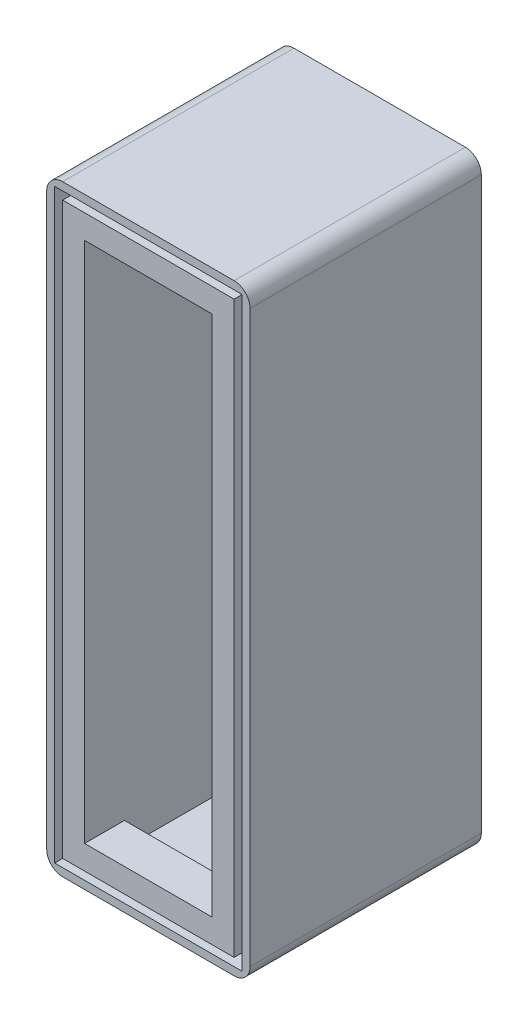
SolidWorks part; units mm, degrees
ref_plane "Front Plane" through (0, 0, 0) normal (0, 0, 1) x (1, 0, 0)
ref_plane "Top Plane" through (0, 0, 0) normal (0, 1, 0) x (1, 0, 0)
ref_plane "Right Plane" through (0, 0, 0) normal (1, 0, 0) x (0, 0, -1)
sketch "Sketch1" plane through (0, 0, 0) normal (0, 0, 1) x (1, 0, 0)
  line L1 (-5.9539, 27.3478) -> (19.5461, 27.3478)
  line L2 (-5.9539, 27.3478) -> (-5.9539, -48.1522)
  line L3 (-5.9539, -48.1522) -> (19.5461, -48.1522)
  line L4 (19.5461, 27.3478) -> (19.5461, -48.1522)
  dimension "D1" = 75.5
  dimension "D2" = 25.5
extrude "main body" add sketch "Sketch1" along normal blind 29
sketch "Sketch2" plane through (0, 0, 29) normal (0, 0, 1) x (1, 0, 0)
  line L0 (19.5461, -48.1522) -> (19.5461, 27.3478) construction
  line L1 (-1.2039, 25.3478) -> (14.7961, 25.3478)
  line L2 (-1.2039, 25.3478) -> (-1.2039, -46.1522)
  line L3 (-1.2039, -46.1522) -> (14.7961, -46.1522)
  line L4 (14.7961, 25.3478) -> (14.7961, -46.1522)
  line L5 (19.5461, 27.3478) -> (-5.9539, 27.3478) construction
  line L6 (-5.9539, -48.1522) -> (19.5461, -48.1522) construction
  dimension "D1" = 16
  dimension "D2" = 4.75
  dimension "D3" = 2
  dimension "D4" = 2
extrude "battery cut" cut sketch "Sketch2" against normal blind 17
sketch "Sketch3" plane through (0, 0, 0) normal (0, 0, -1) x (-1, 0, 0)
  line L0 (-19.5461, -48.1522) -> (-19.5461, 27.3478) construction
  line L1 (-17.7961, 25.3478) -> (4.2039, 25.3478)
  line L2 (-17.7961, 25.3478) -> (-17.7961, -46.1522)
  line L3 (-17.7961, -46.1522) -> (4.2039, -46.1522)
  line L4 (4.2039, 25.3478) -> (4.2039, -46.1522)
  line L5 (-19.5461, 27.3478) -> (5.9539, 27.3478) construction
  dimension "D1" = 22
  dimension "D2" = 71.5
  dimension "D3" = 1.75
  dimension "D4" = 2
extrude "pcb cut" cut sketch "Sketch3" against normal blind 12
sketch "Sketch4" plane through (0, 0, 0) normal (0, 0, -1) x (-1, 0, 0)
  line L0 (5.9539, 27.3478) -> (5.9539, -48.1522) construction
  line L1 (-18.4211, 16.4728) -> (4.8289, 16.4728)
  line L2 (-18.4211, 16.4728) -> (-18.4211, -47.0272)
  line L3 (-18.4211, -47.0272) -> (4.8289, -47.0272)
  line L4 (4.8289, 16.4728) -> (4.8289, -47.0272)
  line L5 (5.9539, -48.1522) -> (-19.5461, -48.1522) construction
  dimension "D1" = 23.25
  dimension "D2" = 1.125
  dimension "D3" = 1.125
  dimension "D4" = 63.5
extrude "solar cut" cut sketch "Sketch4" against normal blind 2
sketch "Sketch5" plane through (0, 0, 0) normal (0, 0, -1) x (-1, 0, 0)
  line L1 (-17.7961, 25.3478) -> (4.2039, 25.3478)
  line L2 (-17.7961, 25.3478) -> (-17.7961, 16.4728)
  line L3 (-17.7961, 16.4728) -> (4.2039, 16.4728)
  line L4 (4.2039, 25.3478) -> (4.2039, 16.4728)
extrude "solar gap fill" add sketch "Sketch5" against normal blind 2 separate body
sketch "Sketch6" plane through (0, -48.1522, 0) normal (0, -1, 0) x (1, 0, 0)
  line L0 (9.7961, 7.25) -> (3.7961, 7.25) construction
  line L1 (9.7961, 5.5) -> (3.7961, 5.5)
  line L2 (9.7961, 9) -> (3.7961, 9)
  line L3 (17.7961, 12) -> (14.7961, 12) construction
  line L4 (-5.9539, 29) -> (-5.9539, 0) construction
  line L5 (19.5461, 29) -> (19.5461, 0) construction
  arc A0 (9.7961, 5.5) -> (9.7961, 9) centre (9.7961, 7.25) ccw
  arc A1 (3.7961, 9) -> (3.7961, 5.5) centre (3.7961, 7.25) ccw
  point P2 (6.7961, 7.25)
  dimension "D4" = 9.75
  dimension "D5" = 9.75
  dimension "D1" = 3.5
  dimension "D2" = 6
  dimension "D3" = 3
extrude "USB cut" cut sketch "Sketch6" against normal blind 2
sketch "Sketch7" plane through (0, -48.1522, 0) normal (0, -1, 0) x (1, 0, 0)
  line L0 (9.2961, 7.25) -> (4.2961, 7.25) construction
  line L1 (9.2961, 3.75) -> (4.2961, 3.75)
  line L2 (9.2961, 10.75) -> (4.2961, 10.75)
  line L4 (-5.9539, 29) -> (-5.9539, 0) construction
  line L5 (9.7961, 9) -> (3.7961, 9) construction
  line L6 (3.7961, 5.5) -> (9.7961, 5.5) construction
  arc A0 (9.2961, 3.75) -> (9.2961, 10.75) centre (9.2961, 7.25) ccw
  arc A1 (4.2961, 10.75) -> (4.2961, 3.75) centre (4.2961, 7.25) ccw
  point P2 (6.7961, 7.25)
  dimension "D4" = 10.25
  dimension "D1" = 7
  dimension "D2" = 5
  dimension "D3" = 1.75
  dimension "D5" = 1.75
extrude "USB clearance emboss" cut sketch "Sketch7" against normal blind 1
fillet "Fillet1" radius 2 4 edges at (19.5461, 27.3478, 14.5) (-5.9539, 27.3478, 14.5) (19.5461, -48.1522, 14.5) (-5.9539, -48.1522, 14.5)
sketch "Sketch9" plane through (0, 0, 29) normal (0, 0, 1) x (1, 0, 0)
  line L0 (-5.9539, 25.3478) -> (-5.9539, -46.1522) construction
  line L1 (-4.9539, 26.3478) -> (18.5461, 26.3478)
  line L2 (-4.9539, 26.3478) -> (-4.9539, -47.1522)
  line L3 (-4.9539, -47.1522) -> (18.5461, -47.1522)
  line L4 (18.5461, 26.3478) -> (18.5461, -47.1522)
  line L5 (19.5461, -46.1522) -> (19.5461, 25.3478) construction
  line L6 (-3.9539, -48.1522) -> (17.5461, -48.1522) construction
  line L7 (17.5461, 27.3478) -> (-3.9539, 27.3478) construction
  line L9 (-3.9539, 25.3478) -> (17.5461, 25.3478)
  line L10 (-3.9539, 25.3478) -> (-3.9539, -46.1522)
  line L11 (-3.9539, -46.1522) -> (17.5461, -46.1522)
  line L12 (17.5461, 25.3478) -> (17.5461, -46.1522)
  dimension "D1" = 1
  dimension "D2" = 1
  dimension "D3" = 1
  dimension "D4" = 1
  dimension "D5" = 1
  dimension "D6" = 1
  dimension "D7" = 1
  dimension "D8" = 1
extrude "Cut-Extrude7" cut sketch "Sketch9" against normal blind 2
sketch "Sketch10" plane through (0, 0, 29) normal (0, 0, 1) x (1, 0, 0)
  line L0 (14.7961, -46.1522) -> (14.7961, 25.3478) construction
  line L1 (-1.2039, 25.3478) -> (14.7961, 25.3478)
  line L2 (-1.2039, 25.3478) -> (-1.2039, 22.3478)
  line L3 (-1.2039, 22.3478) -> (14.7961, 22.3478)
  line L4 (14.7961, 25.3478) -> (14.7961, 22.3478)
  line L6 (-1.2039, -46.1522) -> (14.7961, -46.1522)
  line L7 (-1.2039, -46.1522) -> (-1.2039, -43.1522)
  line L8 (-1.2039, -43.1522) -> (14.7961, -43.1522)
  line L9 (14.7961, -46.1522) -> (14.7961, -43.1522)
  dimension "D1" = 3
  dimension "D2" = 3
extrude "Boss-Extrude3" add sketch "Sketch10" against normal blind 5
sketch "Sketch11" plane through (0, 0, 2) normal (0, 0, 1) x (1, 0, 0)
  line L0 (-4.2039, 25.3478) -> (17.7961, 25.3478) construction
  line L1 (17.5914, 25.3478) -> (-4.2039, 25.3478)
  line L2 (17.5914, 25.3478) -> (17.5914, 15.9728)
  line L3 (17.5914, 15.9728) -> (-4.2039, 15.9728)
  line L4 (-4.2039, 25.3478) -> (-4.2039, 15.9728)
  line L5 (-4.2039, 16.4728) -> (-4.2039, -46.1522) construction
  line L6 (17.7961, 16.4728) -> (-4.2039, 16.4728) construction
  dimension "D1" = 0.5
extrude "Boss-Extrude4" add sketch "Sketch11" along normal blind 1
